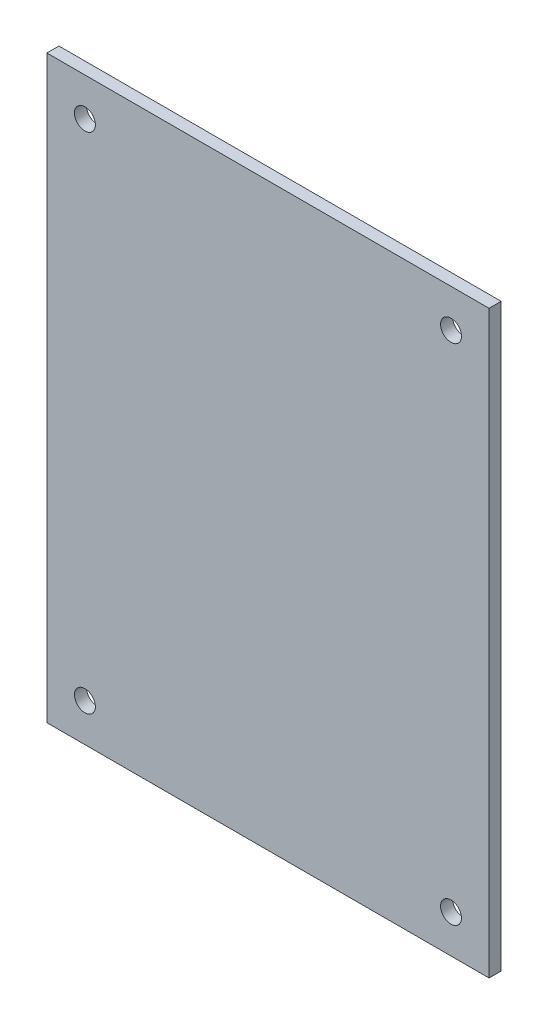
SolidWorks part; units mm, degrees
material "Acrylic (Medium-high impact)"
ref_plane "Front" through (0, 0, 0) normal (0, 0, 1) x (1, 0, 0)
ref_plane "Top" through (0, 0, 0) normal (0, 1, 0) x (1, 0, 0)
ref_plane "Right" through (0, 0, 0) normal (1, 0, 0) x (0, 0, -1)
sketch "Sketch1" plane through (0, 0, 0) normal (0, 0, 1) x (1, 0, 0)
  line L1 (0, 0) -> (116.2, 0)
  line L2 (0, 0) -> (0, 152.4)
  line L3 (0, 152.4) -> (116.2, 152.4)
  line L4 (116.2, 0) -> (116.2, 152.4)
  dimension "D1" = 152.4
  dimension "D2" = 116.2
extrude "Boss-Extrude1" add sketch "Sketch1" along normal blind 3.175 contours L2 L3 L4 L1
hole_wizard "M5 Clearance Hole1" positions "Sketch2" profile "Sketch3" hole size "M5" standard "ANSI Metric" end condition up to next
sketch "Sketch2" plane through (0, 0, 3.175) normal (0, 0, 1) x (1, 0, 0)
  line L1 (0, 152.4) -> (116.2, 152.4) construction
  line L2 (10, 152.4) -> (10, 142.4) construction
  line L3 (10, 142.4) -> (0, 142.4) construction
  line L4 (0, 0) -> (0, 152.4) construction
  line L6 (106.2, 152.4) -> (106.2, 142.4) construction
  line L7 (106.2, 142.4) -> (116.2, 142.4) construction
  line L8 (116.2, 0) -> (116.2, 152.4) construction
  line L10 (10, 0) -> (10, 10) construction
  line L11 (0, 0) -> (116.2, 0) construction
  line L12 (10, 10) -> (0, 10) construction
  line L14 (106.2, 0) -> (106.2, 10) construction
  line L15 (106.2, 10) -> (116.2, 10) construction
  point P0 (10, 142.4)
  point P2 (106.2, 142.4)
  point P4 (106.2, 10)
  point P6 (10, 10)
  dimension "D1" = 10
sketch "Sketch3" plane through (10, 142.4, 3.175) normal (1, 0, 0) x (0, -1, 0)
  line L0 (0, 0) -> (0, 3.175)
  line L1 (0, 3.175) -> (2.75, 3.175)
  line L2 (2.75, 3.175) -> (2.75, 0)
  line L5 (2.75, 0) -> (0, 0)
  line L11 (0, -6.35) -> (0, 107.95) construction
  dimension "Thru Hole Dia." = 5.5
  dimension "Thru Hole Depth" = 3.175
